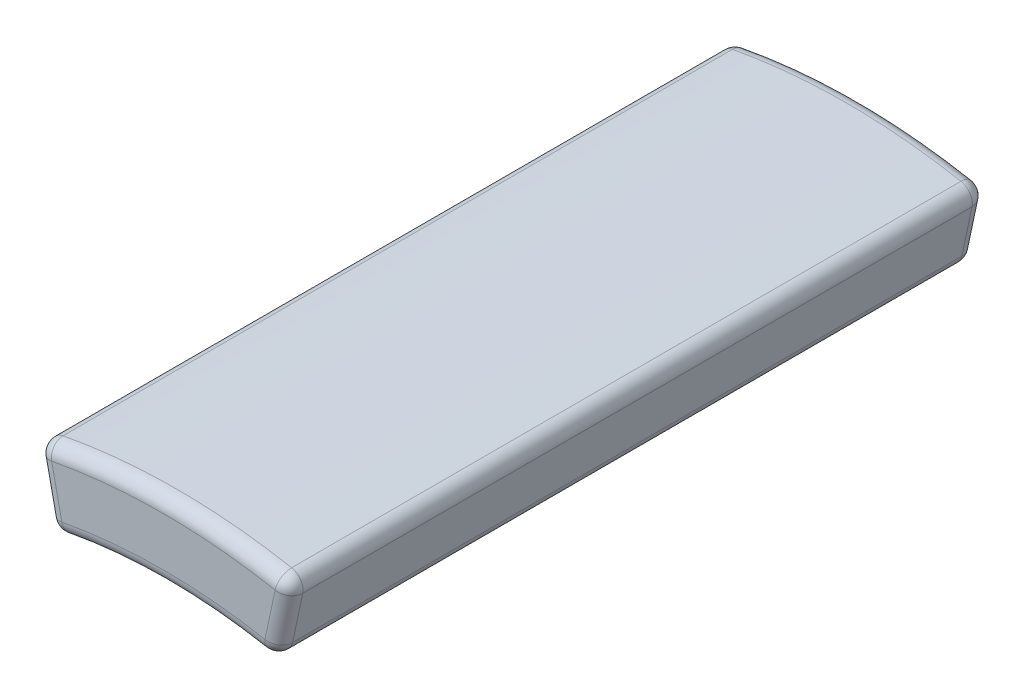
SolidWorks part; units mm, degrees
material "NdFeB N52"
ref_plane "Front Plane" through (0, 0, 0) normal (0, 0, 1) x (1, 0, 0)
ref_plane "Top Plane" through (0, 0, 0) normal (0, 1, 0) x (1, 0, 0)
ref_plane "Right Plane" through (0, 0, 0) normal (1, 0, 0) x (0, 0, -1)
sketch "Sketch4" plane through (0, 0, 0) normal (0, 0, 1) x (1, 0, 0)
  line L0 (-3.68, 0.7132) -> (-3.2226, -1.4387)
  line L1 (3.2226, -1.4387) -> (3.68, 0.7132)
  line L2 (0, 1.1) -> (0, -1.1) construction
  arc A0 (-3.2226, -1.4387) -> (3.2226, -1.4387) centre (0, -16.6) cw
  arc A1 (-3.68, 0.7132) -> (3.68, 0.7132) centre (0, -16.6) cw
  point P1 (0, 0)
  point P6 (0, -1.1)
  dimension "D3" = 15.5
  dimension "D4" = 17.7
  dimension "D1" = 24
  dimension "D2" = 2.2
extrude "Boss-Extrude2" add sketch "Sketch4" along normal mid plane 20 separate body
fillet "Fillet1" radius 0.4 12 edges at (3.2226, -1.4387, 0) (3.68, 0.7132, 0) (-3.68, 0.7132, 0) (-3.2226, -1.4387, 0) (-3.4513, -0.3627, 10) (0, 1.1, 10) (3.4513, -0.3627, 10) (0, -1.1, 10) (3.4513, -0.3627, -10) (0, 1.1, -10) (-3.4513, -0.3627, -10) (0, -1.1, -10)
sketch "Sketch5" [suppressed] plane through (0, 0, 0) normal (0, 0, 1) x (1, 0, 0)
  line L0 (-5.3121, 1.0667) -> (-4.6364, -2.1123) construction
  line L1 (4.6364, -2.1123) -> (5.3121, 1.0667) construction
  arc A0 (-4.9743, -0.5228) -> (4.9743, -0.5228) centre (0, -23.925) cw
  arc A1 (4.6364, -2.1123) -> (-4.6364, -2.1123) centre (0, -23.925) ccw construction
split line "Magnetization split line" [suppressed]
